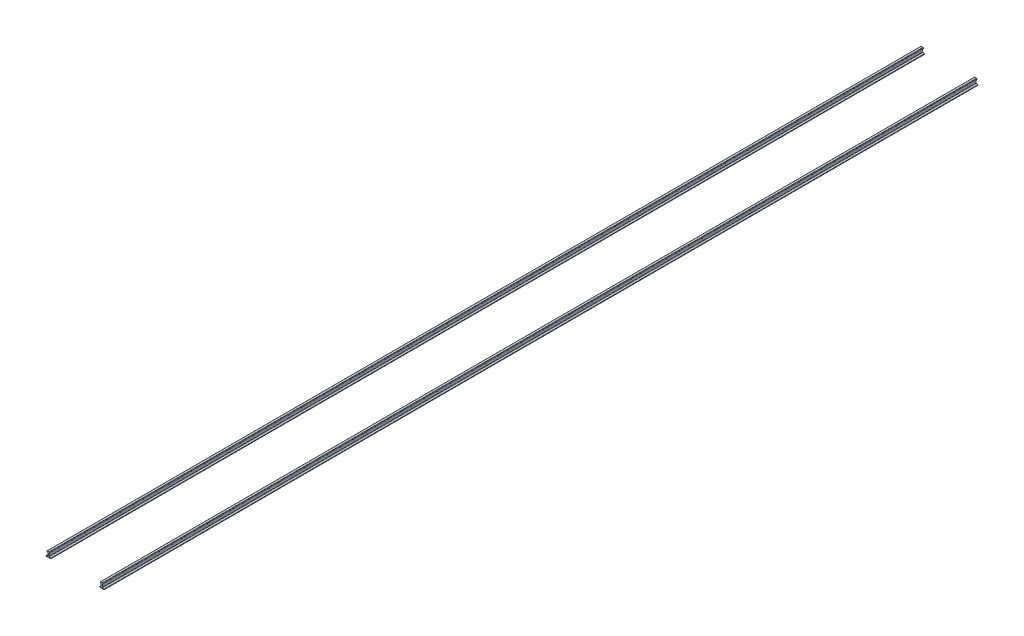
SolidWorks part; units mm, degrees
ref_plane "前视基准面" through (0, 0, 0) normal (0, 0, 1) x (1, 0, 0)
ref_plane "上视基准面" through (0, 0, 0) normal (0, 1, 0) x (1, 0, 0)
ref_plane "右视基准面" through (0, 0, 0) normal (1, 0, 0) x (0, 0, -1)
sketch "草图1" plane through (0, 0, 0) normal (0, 0, 1) x (1, 0, 0)
  line L0 (0, -1000) -> (0, 49000) construction
  line L1 (-35, -1000.4455) -> (-35, 48999.5545) construction
  line L2 (35, -1000.1485) -> (35, 48999.8515) construction
  line L3 (-65, -895.965) -> (-65, 49104.035) construction
  line L4 (67, -918.509) -> (67, 49081.491) construction
  line L5 (-15, -968.6067) -> (-15, 49031.3933) construction
  line L6 (15, -969.4417) -> (15, 49030.5583) construction
  line L7 (-1051.2415, 49.6) -> (48948.7585, 49.6) construction
  line L8 (-1057, -54.6) -> (48943, -54.6) construction
  line L9 (-35, 49.6) -> (-35, 83.5)
  line L10 (-1000, 0) -> (49000, 0) construction
  line L11 (-35, 83.5) -> (35, 83.5)
  line L12 (35, 83.5) -> (35, 49.6)
  line L13 (-35, 49.6) -> (365, -50.4) construction
  line L14 (35, 49.6) -> (-365, -50.4) construction
  line L15 (-35, 49.6) -> (-15, 44.6)
  line L16 (35, 49.6) -> (15, 44.6)
  line L17 (-65, -68.5) -> (67, -68.5)
  line L18 (-15, 44.6) -> (-15, -42.1)
  line L19 (15, 44.6) -> (15, -41.6)
  line L20 (-65, -54.6) -> (-15, -42.1)
  line L21 (67, -54.6) -> (67, -68.5)
  line L22 (15, -41.6) -> (67, -54.6)
  line L23 (-65, -54.6) -> (-65, -68.5)
  dimension "D1" = 35
  dimension "D2" = 35
  dimension "D3" = 65
  dimension "D4" = 67
  dimension "D5" = 15
  dimension "D6" = 15
  dimension "D7" = 49.6
  dimension "D9" = 83.5
  dimension "D10" = 100
  dimension "D11" = 400
  dimension "D12" = 100
  dimension "D13" = 400
  dimension "D14" = 152
  dimension "D16" = 54.6
extrude "拉伸1" add sketch "草图1" against normal blind 24600
fillet "圆角1" radius 10 2 edges at (-15, -42.1, -12300) (15, -41.6, -12300)
fillet "圆角2" radius 8 2 edges at (-15, 44.6, -12300) (15, 44.6, -12300)
fillet "圆角3" radius 3 2 edges at (35, 49.6, -12300) (-35, 49.6, -12300)
fillet "圆角4" radius 10 2 edges at (-35, 83.5, -12300) (35, 83.5, -12300)
fillet "圆角5" radius 3 2 edges at (-65, -54.6, -12300) (67, -54.6, -12300)
pattern_linear "阵列(线性)1" count 2 spacing 1505 along (-1, 0, 0) of bodies 101
